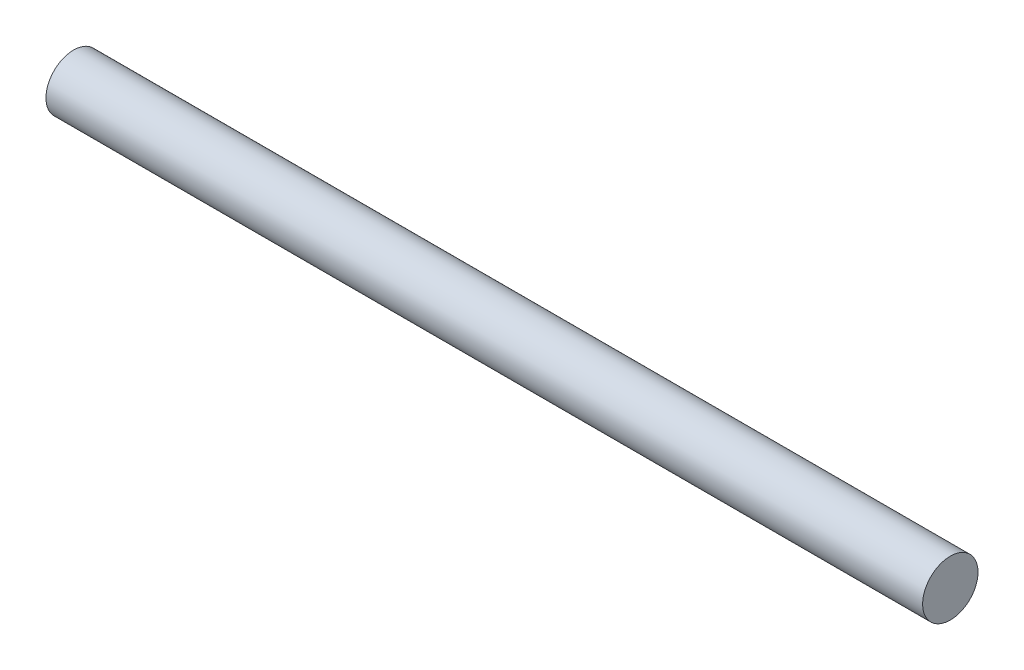
SolidWorks part; units mm, degrees
ref_plane "Front Plane" through (0, 0, 0) normal (0, 0, 1) x (1, 0, 0)
ref_plane "Top Plane" through (0, 0, 0) normal (0, 1, 0) x (1, 0, 0)
ref_plane "Right Plane" through (0, 0, 0) normal (1, 0, 0) x (0, 0, -1)
sketch "Sketch1" plane through (0, 0, 0) normal (1, 0, 0) x (0, 0, -1)
  circle A0 centre (0, 0) radius 50
  dimension "D1" = 100
extrude "Boss-Extrude1" add sketch "Sketch1" along normal blind 1417.329 and the other way blind 165.6572
